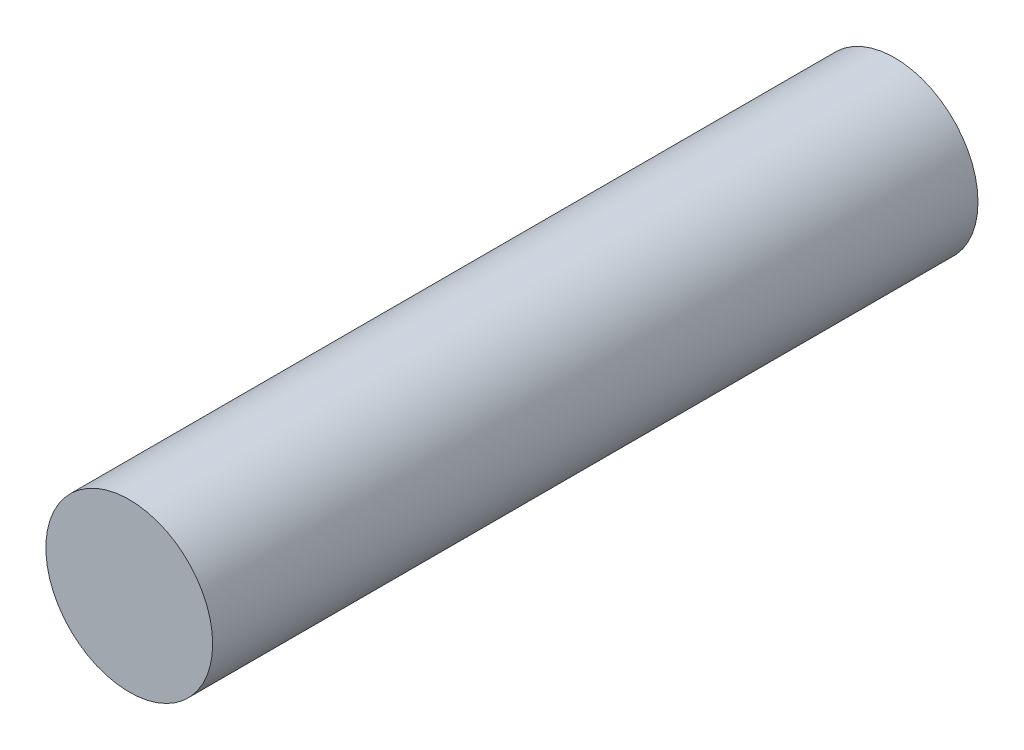
SolidWorks part; units mm, degrees
ref_plane "Спереди" through (0, 0, 0) normal (0, 0, 1) x (1, 0, 0)
ref_plane "Сверху" through (0, 0, 0) normal (0, 1, 0) x (1, 0, 0)
ref_plane "Справа" through (0, 0, 0) normal (1, 0, 0) x (0, 0, -1)
sketch "Эскиз1" plane through (0, 0, 0) normal (0, 0, 1) x (1, 0, 0)
  circle A0 centre (0, 0) radius 2.5
  dimension "D1" = 5
extrude "Бобышка-Вытянуть1" add sketch "Эскиз1" along normal blind 22.94
